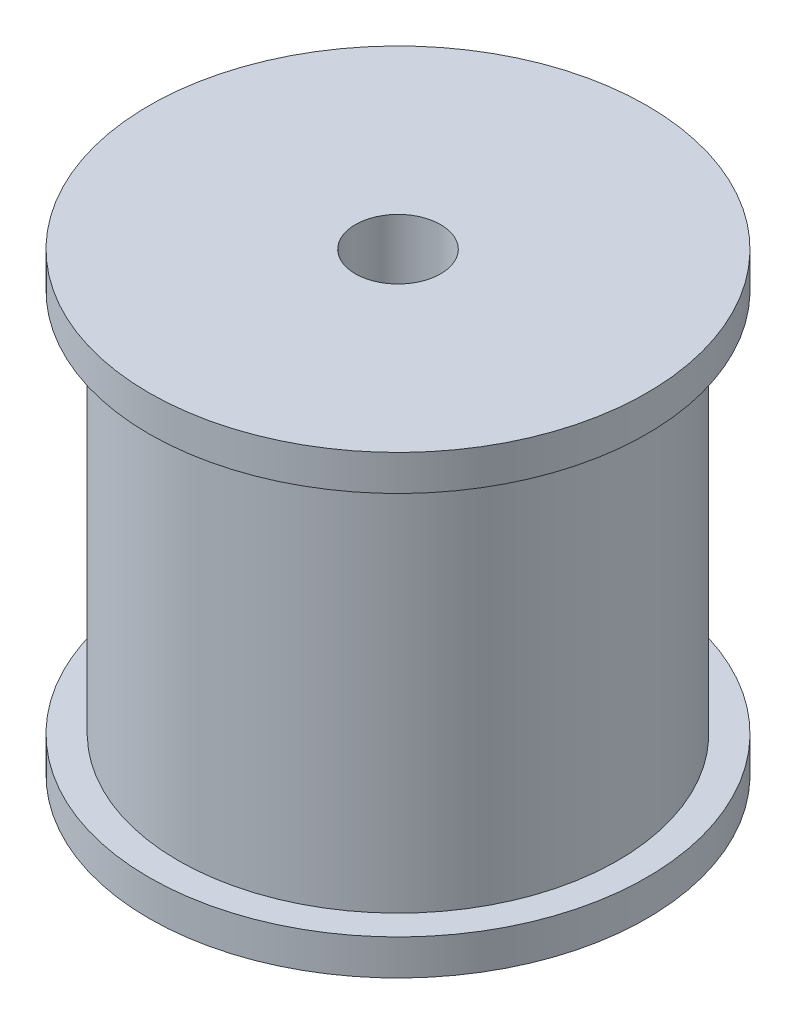
SolidWorks part; units mm, degrees
ref_plane "前视基准面" through (0, 0, 0) normal (0, 0, 1) x (1, 0, 0)
ref_plane "上视基准面" through (0, 0, 0) normal (0, 1, 0) x (1, 0, 0)
ref_plane "右视基准面" through (0, 0, 0) normal (1, 0, 0) x (0, 0, -1)
other "Configuration Table"
sketch "草图1" plane through (0, 0, 0) normal (0, 1, 0) x (1, 0, 0)
  circle A0 centre (0, 0) radius 15.45
  dimension "D1" = 30.9
extrude "凸台-拉伸1" add sketch "草图1" along normal mid plane 27
sketch "草图2" plane through (0, 13.5, 0) normal (0, 1, 0) x (1, 0, 0)
  circle A0 centre (0, 0) radius 17.5
  dimension "D1" = 35
extrude "凸台-拉伸2" add sketch "草图2" along normal blind 2.5
sketch "草图3" plane through (0, -13.5, 0) normal (0, -1, 0) x (1, 0, 0)
  circle A0 centre (0, 0) radius 17.5
extrude "凸台-拉伸3" add sketch "草图3" along normal blind 2.5
sketch "草图4" plane through (0, 16, 0) normal (0, 1, 0) x (1, 0, 0)
  circle A0 centre (0, 0) radius 3
  dimension "D1" = 6
extrude "切除-拉伸1" cut sketch "草图4" against normal through all
